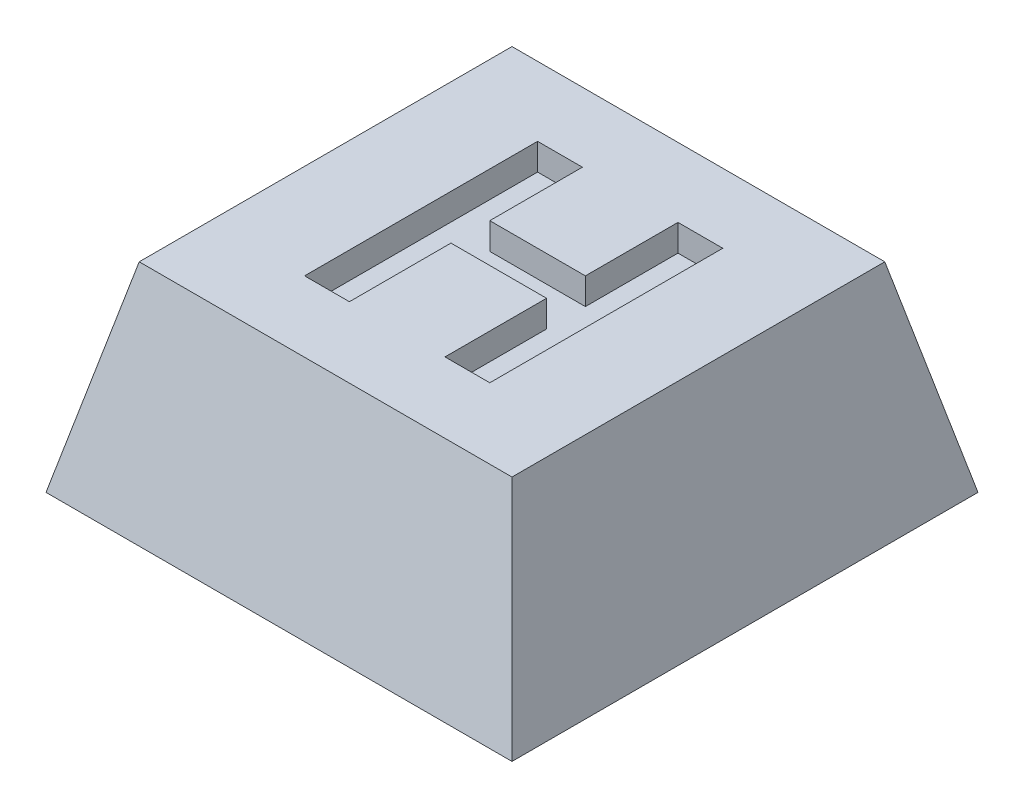
SolidWorks part; units mm, degrees
ref_plane "Front Plane" through (0, 0, 0) normal (0, 0, 1) x (1, 0, 0)
ref_plane "Top Plane" through (0, 0, 0) normal (0, 1, 0) x (1, 0, 0)
ref_plane "Right Plane" through (0, 0, 0) normal (1, 0, 0) x (0, 0, -1)
sketch "Sketch1" plane through (0, 0, 0) normal (0, 1, 0) x (1, 0, 0)
  line L1 (0, 0) -> (7, 0)
  line L2 (0, 0) -> (0, 7)
  line L3 (0, 7) -> (7, 7)
  line L4 (7, 0) -> (7, 7)
  dimension "D1" = 7
  dimension "D2" = 7
extrude "Boss-Extrude1" add sketch "Sketch1" along normal blind 3
sketch "Sketch2" plane through (0, 0, 0) normal (0, 0, 1) x (1, 0, 0)
  line L0 (0, 0) -> (0.7, 3)
  line L1 (0, 3) -> (7, 3) construction
  line L2 (0.7, 3) -> (0, 3)
  line L3 (0, 3) -> (0, 0)
  line L4 (7, 0) -> (6.3, 3)
  line L5 (6.3, 3) -> (7, 3)
  line L6 (7, 3) -> (7, 0)
  dimension "D1" = 0.7
  dimension "D2" = 0.7
extrude "Cut-Extrude1" cut sketch "Sketch2" against normal blind 7
sketch "Sketch3" plane through (0, 0, 0) normal (1, 0, 0) x (0, 0, -1)
  line L0 (0, 0) -> (0.7, 3)
  line L1 (7, 3) -> (0, 3) construction
  line L2 (0.7, 3) -> (0, 3)
  line L3 (0, 3) -> (0, 0)
  line L4 (7, 3) -> (6.3, 3)
  line L5 (6.3, 3) -> (7, 0)
  line L6 (7, 3) -> (7, 0)
  dimension "D1" = 0.7
  dimension "D2" = 0.7
extrude "Cut-Extrude2" cut sketch "Sketch3" along normal blind 11
sketch "Sketch4" plane through (0, 0, 0) normal (0, -1, 0) x (1, 0, 0)
  line L0 (3.5, 0) -> (3.5, -7) construction
  line L1 (0, 0) -> (7, 0) construction
  line L2 (7, -7) -> (0, -7) construction
  line L3 (0, -3.5) -> (7, -3.5) construction
  line L4 (0, -7) -> (0, 0) construction
  line L5 (7, 0) -> (7, -7) construction
  circle A0 centre (3.5, -3.5) radius 1.8
  dimension "D1" = 3.6
extrude "Cut-Extrude3" cut sketch "Sketch4" against normal blind 0.8
sketch "Sketch6" plane through (0, 3, 0) normal (0, 1, 0) x (1, 0, 0)
  text T0 "H" font "Arial" height 3.5
extrude "Cut-Extrude4" cut sketch "Sketch6" against normal blind 0.4
